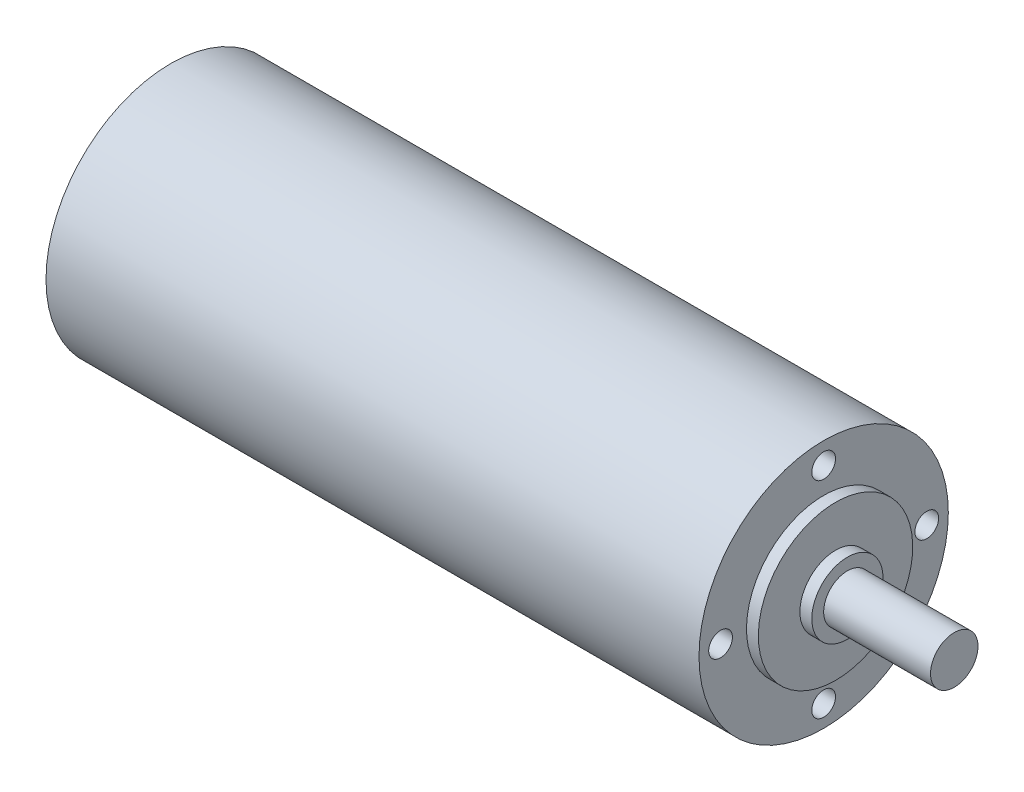
SolidWorks part; units mm, degrees
ref_plane "Front Plane" through (0, 0, 0) normal (0, 0, 1) x (1, 0, 0)
ref_plane "Top Plane" through (0, 0, 0) normal (0, 1, 0) x (1, 0, 0)
ref_plane "Right Plane" through (0, 0, 0) normal (1, 0, 0) x (0, 0, -1)
sketch "Sketch1" plane through (0, 0, 0) normal (0, 0, 1) x (1, 0, 0)
  line L0 (0, 0) -> (132, 0)
  line L1 (132, 0) -> (132, 4)
  line L2 (132, 4) -> (114, 4)
  line L3 (114, 4) -> (114, 6)
  line L4 (114, 6) -> (112, 6)
  line L5 (112, 6) -> (112, 13)
  line L6 (112, 13) -> (110, 13)
  line L7 (110, 13) -> (110, 21)
  line L8 (110, 21) -> (0, 21)
  line L9 (0, 21) -> (0, 0)
  dimension "D1" = 21
  dimension "D2" = 13
  dimension "D3" = 6
  dimension "D4" = 4
  dimension "D5" = 110
  dimension "D6" = 2
  dimension "D7" = 2
  dimension "D8" = 18
revolve "Revolve1" add sketch "Sketch1" angle 360 about L0
sketch "Sketch2" plane through (110, 0, 0) normal (1, 0, 0) x (0, 0, -1)
  circle A0 centre (0, 17.3658) radius 2
  circle A1 centre (17.3658, 0) radius 2
  circle A2 centre (0, -17.3658) radius 2
  circle A3 centre (-17.3658, 0) radius 2
  point P2 (-25.1646, -11.3798)
  point P4 (0, 0)
  point P12 (0, 0)
  dimension "D2" = 4
  dimension "D1" = 17.3658
  dimension "D3" = 4
extrude "Cut-Extrude1" cut sketch "Sketch2" against normal blind 10
